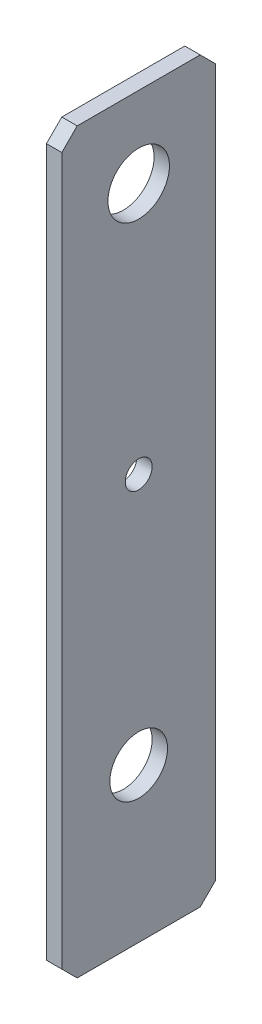
SolidWorks part; units mm, degrees
ref_plane "Front Plane" through (0, 0, 0) normal (0, 0, 1) x (1, 0, 0)
ref_plane "Top Plane" through (0, 0, 0) normal (0, 1, 0) x (1, 0, 0)
ref_plane "Right Plane" through (0, 0, 0) normal (1, 0, 0) x (0, 0, -1)
sketch "Sketch1" plane through (0, 0, 0) normal (1, 0, 0) x (0, 0, -1)
  line L1 (-10, -48) -> (10, -48)
  line L2 (-10, -48) -> (-10, 48)
  line L3 (-10, 48) -> (10, 48)
  line L4 (10, -48) -> (10, 48)
  line L5 (-10, -48) -> (10, 48) construction
  line L6 (-10, 48) -> (10, -48) construction
  point P0 (0, 0)
  dimension "D1" = 96
  dimension "D2" = 20
extrude "Boss-Extrude2" add sketch "Sketch1" along normal blind 2
sketch "Sketch3" plane through (2, 0, 0) normal (1, 0, 0) x (0, 0, -1)
  line L0 (-10, -48) -> (10, -48) construction
  line L1 (10, 48) -> (-10, 48) construction
  circle A0 centre (0, 4.75) radius 1.75
  circle A1 centre (0, 37.5) radius 4
  circle A2 centre (0, -28) radius 3.75
  point P9 (0, 0)
  dimension "D1" = 7.5
  dimension "D2" = 3.5
  dimension "D3" = 8
  dimension "D4" = 32.75
  dimension "D5" = 20
  dimension "D6" = 10.5
extrude "Cut-Extrude1" cut sketch "Sketch3" against normal through all
chamfer "Chamfer1" distance 2 angle 45 4 edges at (1, -48, 10) (1, -48, -10) (1, 48, -10) (1, 48, 10)
